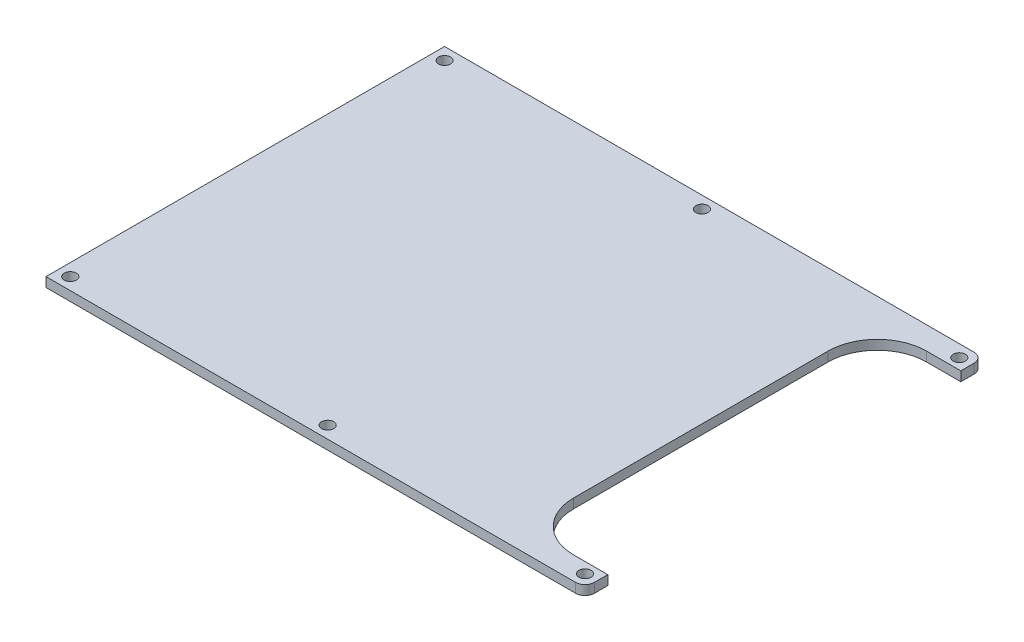
SolidWorks part; units mm, degrees
ref_plane "Front Plane" through (0, 0, 0) normal (0, 0, 1) x (1, 0, 0)
ref_plane "Top Plane" through (0, 0, 0) normal (0, 1, 0) x (1, 0, 0)
ref_plane "Right Plane" through (0, 0, 0) normal (1, 0, 0) x (0, 0, -1)
sketch "Sketch1" plane through (0, 0, 0) normal (0, 1, 0) x (1, 0, 0)
  line L1 (-71, -52.5) -> (71, -52.5)
  line L2 (-71, -52.5) -> (-71, 52.5)
  line L3 (-71, 52.5) -> (71, 52.5)
  line L4 (71, -52.5) -> (71, 52.5)
  line L5 (-71, -52.5) -> (71, 52.5) construction
  line L6 (-71, 52.5) -> (71, -52.5) construction
  point P0 (0, 0)
  dimension "D1" = 105
  dimension "D2" = 142
extrude "Boss-Extrude1" add sketch "Sketch1" along normal blind 2.5
sketch "Sketch2" plane through (0, 2.5, 0) normal (0, 1, 0) x (1, 0, 0)
  line L3 (-67.8, 49.3) -> (-67.8, -49.3) construction
  line L5 (71, -52.5) -> (71, 52.5) construction
  line L6 (71, 46.5) -> (49, 46.5)
  line L7 (71, 46.5) -> (71, -46.5)
  line L8 (71, -46.5) -> (49, -46.5)
  line L9 (49, 46.5) -> (49, -46.5)
  circle A0 centre (-67.8, 49.3) radius 1.6
  circle A1 centre (0, 49.3) radius 1.6
  circle A2 centre (0, -49.3) radius 1.6
  circle A3 centre (-67.8, -49.3) radius 1.6
  circle A4 centre (67.8, 49.3) radius 1.6
  circle A5 centre (67.8, -49.3) radius 1.6
  point P4 (-67.8, 0)
  point P16 (49, 0)
  dimension "D1" = 3.2
  dimension "D4" = 135.6
  dimension "D5" = 98.6
  dimension "D6" = 22
  dimension "D7" = 93
  dimension "D2" = 3
  dimension "D3" = 2
extrude "Cut-Extrude1" cut sketch "Sketch2" against normal up to next
fillet "Fillet1" radius 13 2 edges at (49, 1.25, 46.5) (49, 1.25, -46.5)
fillet "Fillet2" radius 2.5 2 edges at (71, 1.25, -52.5) (71, 1.25, 52.5)
